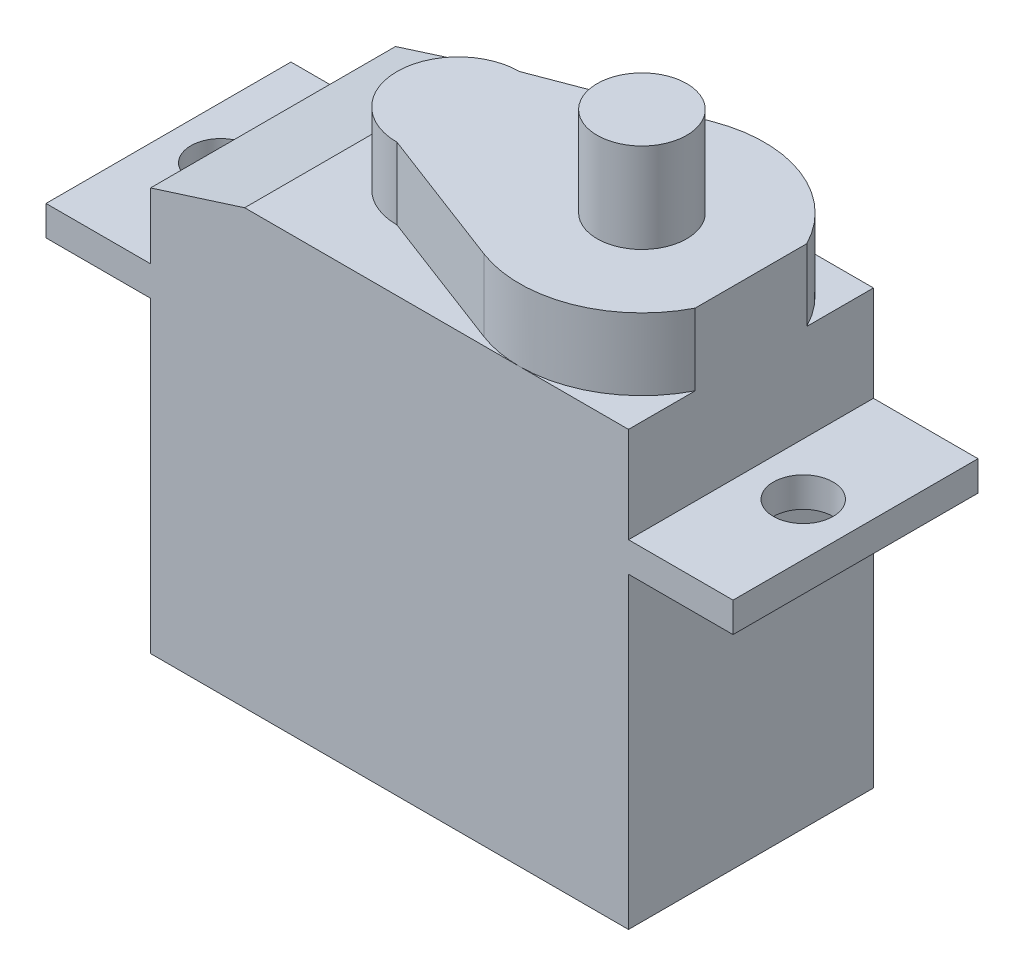
SolidWorks part; units mm, degrees
ref_plane "前视基准面" through (0, 0, 0) normal (0, 0, 1) x (1, 0, 0)
ref_plane "上视基准面" through (0, 0, 0) normal (0, 1, 0) x (1, 0, 0)
ref_plane "右视基准面" through (0, 0, 0) normal (1, 0, 0) x (0, 0, -1)
other "Configuration Table"
sketch "草图1" plane through (0, 0, 0) normal (0, 1, 0) x (1, 0, 0)
  line L1 (-8, 4.1) -> (8, 4.1)
  line L2 (-8, 4.1) -> (-8, -4.1)
  line L3 (-8, -4.1) -> (8, -4.1)
  line L4 (8, 4.1) -> (8, -4.1)
  line L5 (-8, 4.1) -> (8, -4.1) construction
  line L6 (-8, -4.1) -> (8, 4.1) construction
  point P0 (0, 0)
  dimension "D1" = 8.2
  dimension "D2" = 16
extrude "凸台-拉伸1" add sketch "草图1" along normal blind 10.3
sketch "草图2" plane through (0, 0, 0) normal (0, 1, 0) x (1, 0, 0)
  line L1 (-11.5, 4.1) -> (11.5, 4.1)
  line L2 (-11.5, 4.1) -> (-11.5, -4.1)
  line L3 (-11.5, -4.1) -> (11.5, -4.1)
  line L4 (11.5, 4.1) -> (11.5, -4.1)
  line L5 (-11.5, 4.1) -> (11.5, -4.1) construction
  line L6 (-11.5, -4.1) -> (11.5, 4.1) construction
  point P0 (0, 0)
  dimension "D1" = 8.2
  dimension "D2" = 23
extrude "凸台-拉伸2" add sketch "草图2" along normal blind 1 from offset 10.3
sketch "草图3" plane through (0, 0, 0) normal (0, 1, 0) x (1, 0, 0)
  line L1 (-8, 4.1) -> (8, 4.1)
  line L2 (-8, 4.1) -> (-8, -4.1)
  line L3 (-8, -4.1) -> (8, -4.1)
  line L4 (8, 4.1) -> (8, -4.1)
  line L5 (-8, 4.1) -> (8, -4.1) construction
  line L6 (-8, -4.1) -> (8, 4.1) construction
  point P0 (0, 0)
  dimension "D1" = 16
  dimension "D2" = 8.2
extrude "凸台-拉伸3" add sketch "草图3" along normal blind 14.5
sketch "草图4" plane through (0, 0, 0) normal (0, 1, 0) x (1, 0, 0)
  line L0 (-9.75, 0) -> (9.75, 0) construction
  circle A0 centre (-9.75, 0) radius 1
  circle A1 centre (9.75, 0) radius 1
  point P4 (0, 0)
  dimension "D2" = 2
  dimension "D3" = 2
  dimension "D1" = 19.5
extrude "切除-拉伸1" cut sketch "草图4" along normal blind 14.5
sketch "草图6" plane through (0, 0, 0) normal (0, 1, 0) x (1, 0, 0)
  line L0 (9.75, 0) -> (4.35, 0) construction
  line L1 (8, 4.1) -> (8, -4.1) construction
  line L2 (8, 1.8675) -> (8, -1.8675)
  line L3 (-1.8, 2.05) -> (2.8943, 3.8329)
  line L4 (-1.8, -2.05) -> (2.8943, -3.8329)
  arc A0 (8, 1.8675) -> (2.8943, 3.8329) centre (4.35, 0) ccw
  arc A1 (-1.8, 2.05) -> (-1.8, -2.05) centre (-1.8, 0) ccw
  arc A2 (2.8943, -3.8329) -> (8, -1.8675) centre (4.35, 0) ccw
  dimension "D1" = 5.4
  dimension "D2" = 1.8
extrude "凸台-拉伸4" add sketch "草图6" along normal blind 16.9
sketch "草图7" plane through (0, 0, 0) normal (0, 1, 0) x (1, 0, 0)
  line L0 (9.75, 0) -> (4.35, 0) construction
  circle A0 centre (4.35, 0) radius 1.5
  dimension "D2" = 3
  dimension "D1" = 5.4
extrude "凸台-拉伸5" add sketch "草图7" along normal blind 19.9
sketch "草图8" plane through (0, 0, 0) normal (0, 0, 1) x (1, 0, 0)
  line L0 (-8, 14.5) -> (-8, 13.5)
  line L1 (-8, 14.5) -> (-8, 11.3) construction
  line L3 (-8, 14.5) -> (4.35, 14.5) construction
  line L5 (-4.85, 14.5) -> (-8, 13.5)
  line L6 (-4.85, 14.5) -> (-8, 14.5)
  dimension "D1" = 1
extrude "切除-拉伸2" cut sketch "草图8" against normal blind 10 and the other way blind 10
